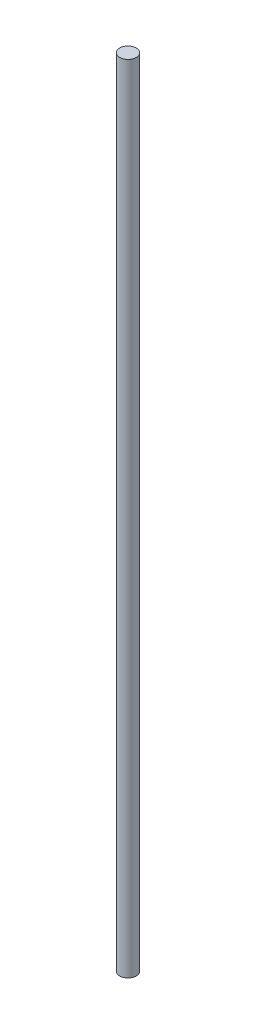
SolidWorks part; units mm, degrees
ref_plane "Front Plane" through (0, 0, 0) normal (0, 0, 1) x (1, 0, 0)
ref_plane "Top Plane" through (0, 0, 0) normal (0, 1, 0) x (1, 0, 0)
ref_plane "Right Plane" through (0, 0, 0) normal (1, 0, 0) x (0, 0, -1)
sketch "Sketch1" plane through (0, 0, 0) normal (0, 1, 0) x (1, 0, 0)
  circle A0 centre (0, 0) radius 4
  dimension "D1" = 8
extrude "Boss-Extrude1" add sketch "Sketch1" along normal blind 386.26
equation "\"d\" = 8"
equation "\"l\"= 379.9 + 6.36"
equation "\"D1@Boss-Extrude1\"=\"l\""
equation "\"D1@Sketch1\"=\"d\""
